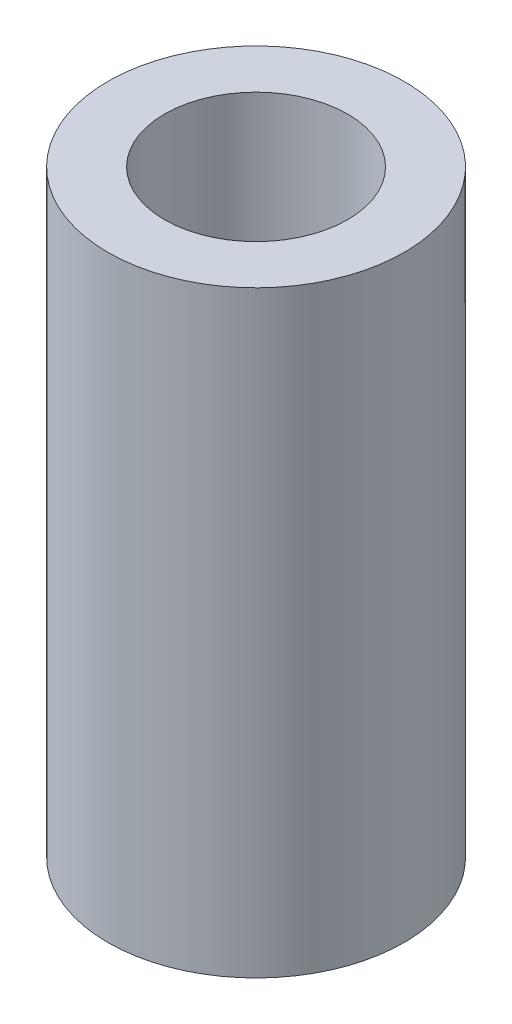
SolidWorks part; units mm, degrees
ref_plane "Front Plane" through (0, 0, 0) normal (0, 0, 1) x (1, 0, 0)
ref_plane "Top Plane" through (0, 0, 0) normal (0, 1, 0) x (1, 0, 0)
ref_plane "Right Plane" through (0, 0, 0) normal (1, 0, 0) x (0, 0, -1)
sketch "Sketch1" plane through (0, 0, 0) normal (0, 1, 0) x (1, 0, 0)
  circle A0 centre (0, 0) radius 3.2375
  circle A1 centre (0, 0) radius 5.2375
  dimension "D1" = 6.475
  dimension "D2" = 2
extrude "Boss-Extrude1" add sketch "Sketch1" along normal blind 21.1346 contours A1 | A0
